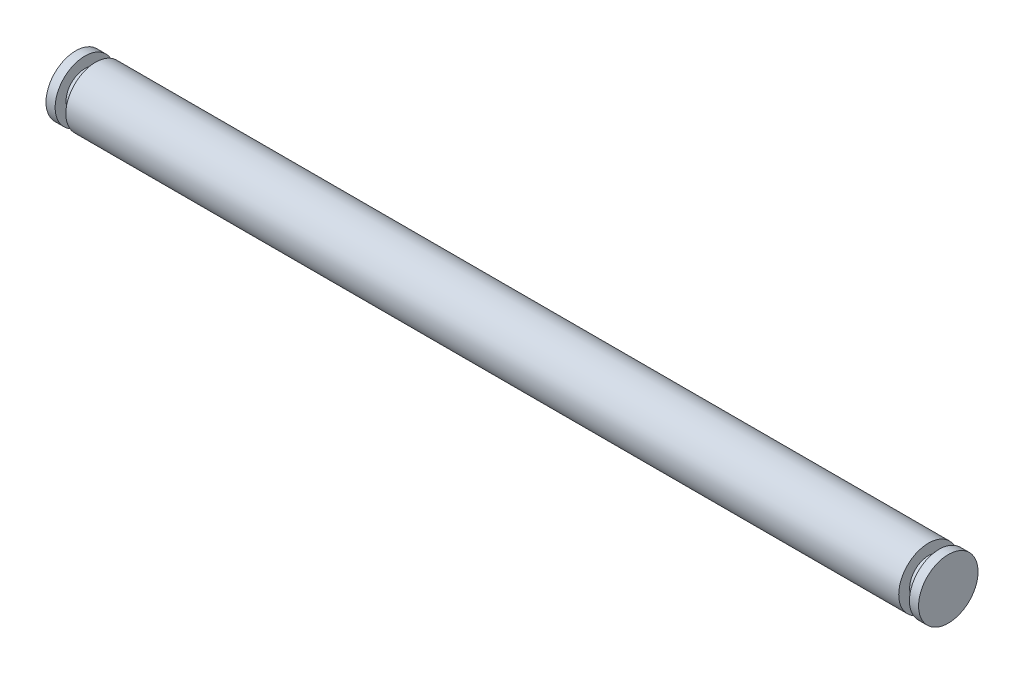
SolidWorks part; units mm, degrees
ref_plane "Front Plane" through (0, 0, 0) normal (0, 0, 1) x (1, 0, 0)
ref_plane "Top Plane" through (0, 0, 0) normal (0, 1, 0) x (1, 0, 0)
ref_plane "Right Plane" through (0, 0, 0) normal (1, 0, 0) x (0, 0, -1)
ref_plane "Plane1" through (0, 0, 0) normal (0, 0, -1) x (-1, 0, 0)
sketch "Sketch1" plane through (0, 0, 0) normal (0, 0, -1) x (-1, 0, 0)
  line L0 (-22, 1.5) -> (-22, 0)
  line L1 (-22, 0) -> (22, 0)
  line L2 (22, 0) -> (22, 1.5)
  line L3 (22, 1.5) -> (21.54, 1.5)
  line L4 (21.54, 1.5) -> (21.54, 0.95)
  line L5 (21.54, 0.95) -> (21, 0.95)
  line L6 (21, 0.95) -> (21, 1.5)
  line L7 (21, 1.5) -> (-21, 1.5)
  line L8 (-21, 1.5) -> (-21, 0.95)
  line L9 (-21, 0.95) -> (-21.54, 0.95)
  line L10 (-21.54, 0.95) -> (-21.54, 1.5)
  line L11 (-21.54, 1.5) -> (-22, 1.5)
  line L12 (-22, 0) -> (22, 0) construction
  dimension "D1" = 0.46
  dimension "D2" = 1
  dimension "D3" = 43
  dimension "D4" = 43.54
  dimension "D5" = 44
  dimension "D6" = 0.55
  dimension "D7" = 1.5
revolve "Revolve1" add sketch "Sketch1" angle 360 about L12
